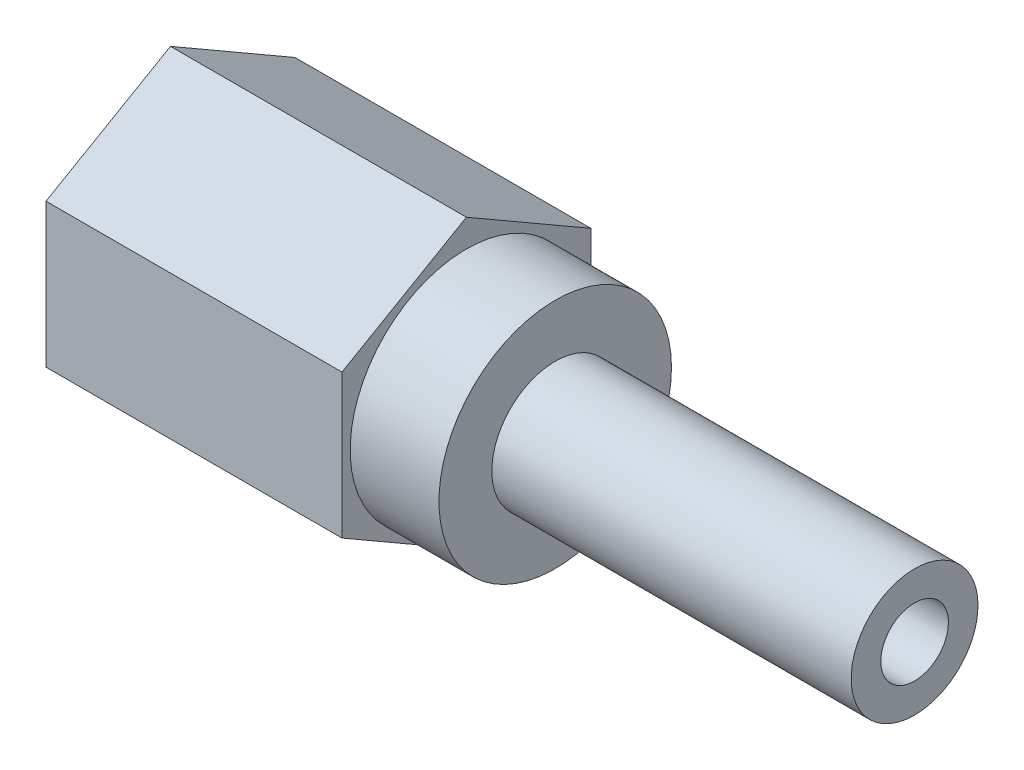
SolidWorks part; units mm, degrees
ref_plane "Front Plane" through (0, 0, 0) normal (1, 0, 0) x (0, 1, 0)
ref_plane "Top Plane" through (0, 0, 0) normal (0, 0, 1) x (0, 1, 0)
ref_plane "Right Plane" through (0, 0, 0) normal (0, 1, 0) x (-1, 0, 0)
sketch "Sketch1" plane through (0, 0, 0) normal (1, 0, 0) x (0, 1, 0)
  line L1 (3.4, 0) -> (1.7, 2.9445)
  line L2 (1.7, 2.9445) -> (-1.7, 2.9445)
  line L3 (-1.7, 2.9445) -> (-3.4, 0)
  line L4 (-3.4, 0) -> (-1.7, -2.9445)
  line L5 (-1.7, -2.9445) -> (1.7, -2.9445)
  line L6 (1.7, -2.9445) -> (3.4, 0)
  circle A0 centre (0, 0) radius 3.4 construction
  dimension "D1" = 6.8
extrude "Boss-Extrude1" add sketch "Sketch1" along normal blind 7
sketch "Sketch2" plane through (7, 0, 0) normal (1, 0, 0) x (0, 1, 0)
  circle A0 centre (0, 0) radius 2.75
  dimension "D1" = 5.5
extrude "Boss-Extrude2" add sketch "Sketch2" along normal blind 2.1
sketch "Sketch3" plane through (9.1, 0, 0) normal (1, 0, 0) x (0, 1, 0)
  circle A0 centre (0, 0) radius 1.5
  dimension "D1" = 3
extrude "Boss-Extrude3" add sketch "Sketch3" along normal blind 8.5
sketch "Sketch4" plane through (0, 0, 0) normal (-1, 0, 0) x (0, -1, 0)
  circle A0 centre (0, 0) radius 1.5
  dimension "D1" = 3
extrude "Cut-Extrude1" cut sketch "Sketch4" against normal blind 5
sketch "Sketch5" plane through (5, 0, 0) normal (-1, 0, 0) x (0, -1, 0)
  circle A0 centre (0, 0) radius 0.8
  dimension "D1" = 1.6
extrude "Cut-Extrude2" cut sketch "Sketch5" against normal through all
